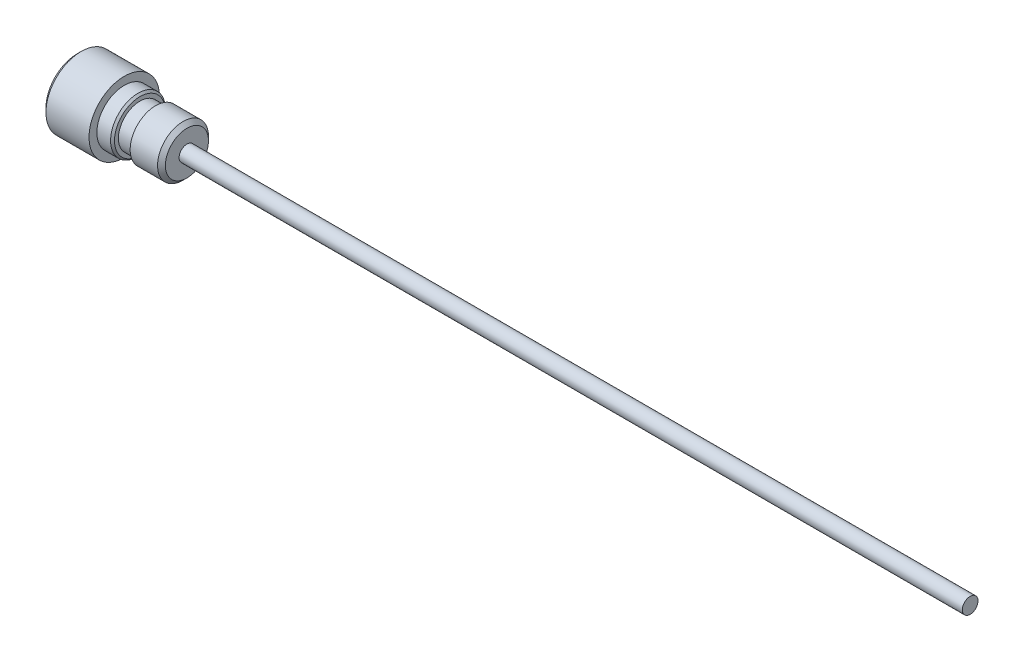
SolidWorks part; units mm, degrees
ref_plane "Alzado" through (0, 0, 0) normal (0, 0, 1) x (1, 0, 0)
ref_plane "Planta" through (0, 0, 0) normal (0, 1, 0) x (1, 0, 0)
ref_plane "Vista lateral" through (0, 0, 0) normal (1, 0, 0) x (0, 0, -1)
sketch "Croquis1" plane through (0, 0, 0) normal (1, 0, 0) x (0, 0, -1)
  circle A0 centre (0, 0) radius 9
  dimension "D1" = 18
extrude "Saliente-Extruir1" add sketch "Croquis1" along normal blind 12
chamfer "Chaflán1" distance 1 angle 45 1 edges at (0, 0, -9)
sketch "Croquis2" plane through (12, 0, 0) normal (1, 0, 0) x (0, 0, -1)
  circle A0 centre (0, 0) radius 7
  dimension "D1" = 14
extrude "Saliente-Extruir2" add sketch "Croquis2" along normal blind 4
sketch "Croquis3" plane through (16, 0, 0) normal (1, 0, 0) x (0, 0, -1)
  circle A0 centre (0, 0) radius 5.5
  dimension "D1" = 11
extrude "Saliente-Extruir3" add sketch "Croquis3" along normal blind 4
sketch "Croquis4" plane through (20, 0, 0) normal (1, 0, 0) x (0, 0, -1)
  circle A0 centre (0, 0) radius 6.5
  dimension "D1" = 13
extrude "Saliente-Extruir4" add sketch "Croquis4" along normal blind 8
chamfer "Chaflán2" distance 1 angle 45 1 edges at (28, 0, -6.5)
sketch "Croquis5" plane through (28, 0, 0) normal (1, 0, 0) x (0, 0, -1)
  circle A0 centre (0, 0) radius 2
  dimension "D1" = 4
extrude "Saliente-Extruir5" add sketch "Croquis5" along normal blind 200
chamfer "Chaflán3" distance 0.5 angle 45 1 edges at (16, 0, -7)
